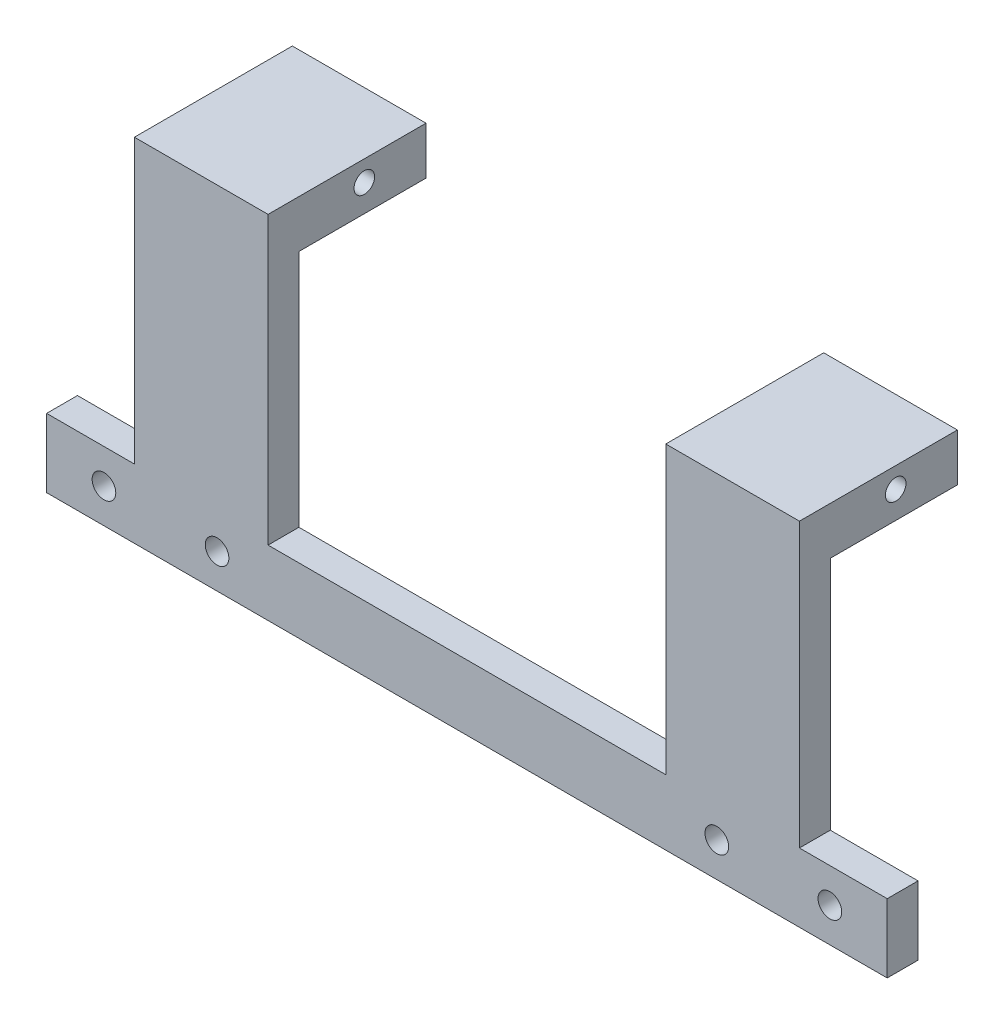
SolidWorks part; units mm, degrees
other "标注1"
sketch "草图3" plane through (73.376, -23.3813, 0) normal (0.2558, -0.756, -0.6025) x (-0.9198, 0.0015, -0.3924)
ref_plane "前视基准面" through (0, 0, 0) normal (0, 0, 1) x (1, 0, 0)
ref_plane "上视基准面" through (0, 0, 0) normal (0, 1, 0) x (1, 0, 0)
ref_plane "右视基准面" through (0, 0, 0) normal (1, 0, 0) x (0, 0, -1)
other "图形1"
other "图形 (闭合) -1"
sketch "草图1" plane through (0, 0, 0) normal (0, 0, 1) x (1, 0, 0)
  line L0 (13.1611, 10.8284) -> (13.1611, -17.0269)
  line L1 (13.1611, -17.0269) -> (51.8389, -17.0269)
  line L2 (51.8389, -17.0269) -> (51.8389, 10.8284)
  line L3 (51.8389, 10.8284) -> (64.8389, 10.8284)
  line L4 (64.8389, 10.8284) -> (64.8389, -16.7)
  line L5 (64.8389, -16.7) -> (73.376, -16.7)
  line L6 (73.376, -16.7) -> (73.376, -23.3813)
  line L7 (73.376, -23.3813) -> (-8.376, -23.3813)
  line L8 (-8.376, -23.3813) -> (-8.376, -16.7)
  line L9 (-8.376, -16.7) -> (0.1611, -16.7)
  line L10 (0.1611, -16.7) -> (0.1611, 10.8284)
  line L11 (0.1611, 10.8284) -> (13.1611, 10.8284)
  line L12 (67.8006, -20.0406) -> (56.8006, -20.0406) construction
  line L13 (56.8006, -20.0406) -> (8.1994, -20.0406) construction
  line L14 (8.1994, -20.0406) -> (-2.8006, -20.0406) construction
  circle A0 centre (-2.8006, -20.0406) radius 1.15
  circle A1 centre (8.1994, -20.0406) radius 1.15
  circle A2 centre (56.8006, -20.0406) radius 1.15
  circle A3 centre (67.8006, -20.0406) radius 1.15
extrude "凸台-拉伸1" add sketch "草图1" along normal blind 3
sketch "草图4" plane through (0, 0, 0) normal (0, 0, -1) x (-1, 0, 0)
  line L0 (-64.8389, 10.8284) -> (-64.8389, 6.2004)
  line L1 (-64.8389, -16.7) -> (-64.8389, 10.8284) construction
  line L2 (-64.8389, 6.2004) -> (-51.8389, 6.2004)
  line L3 (-51.8389, 10.8284) -> (-51.8389, -17.0269) construction
  line L4 (-51.8389, 6.2004) -> (-51.8389, 10.8284)
  line L5 (-51.8389, 10.8284) -> (-64.8389, 10.8284)
  line L6 (-13.1611, 10.8284) -> (-13.1611, 6.2004)
  line L7 (-13.1611, -17.0269) -> (-13.1611, 10.8284) construction
  line L8 (-13.1611, 6.2004) -> (-0.1611, 6.2004)
  line L9 (-0.1611, 10.8284) -> (-0.1611, -16.7) construction
  line L10 (-0.1611, 6.2004) -> (-0.1611, 10.8284)
  line L11 (-0.1611, 10.8284) -> (-13.1611, 10.8284)
extrude "凸台-拉伸2" add sketch "草图4" along normal blind 12.361
sketch "草图5" plane through (0, 0, 0) normal (1, 0, 0) x (0, 0, -1)
  line L2 (12.361, 10.8284) -> (12.361, 8.5144) construction
  line L3 (12.361, 10.8284) -> (12.361, 6.2004) construction
  line L4 (12.361, 8.5144) -> (6.361, 8.5144) construction
  circle A1 centre (6.361, 8.5144) radius 1
sketch "草图6" plane through (64.8389, 0, 0) normal (1, 0, 0) x (0, 0, -1)
  circle A0 centre (6.361, 8.8284) radius 1
extrude "切除-拉伸2" cut sketch "草图6" against normal blind 200
